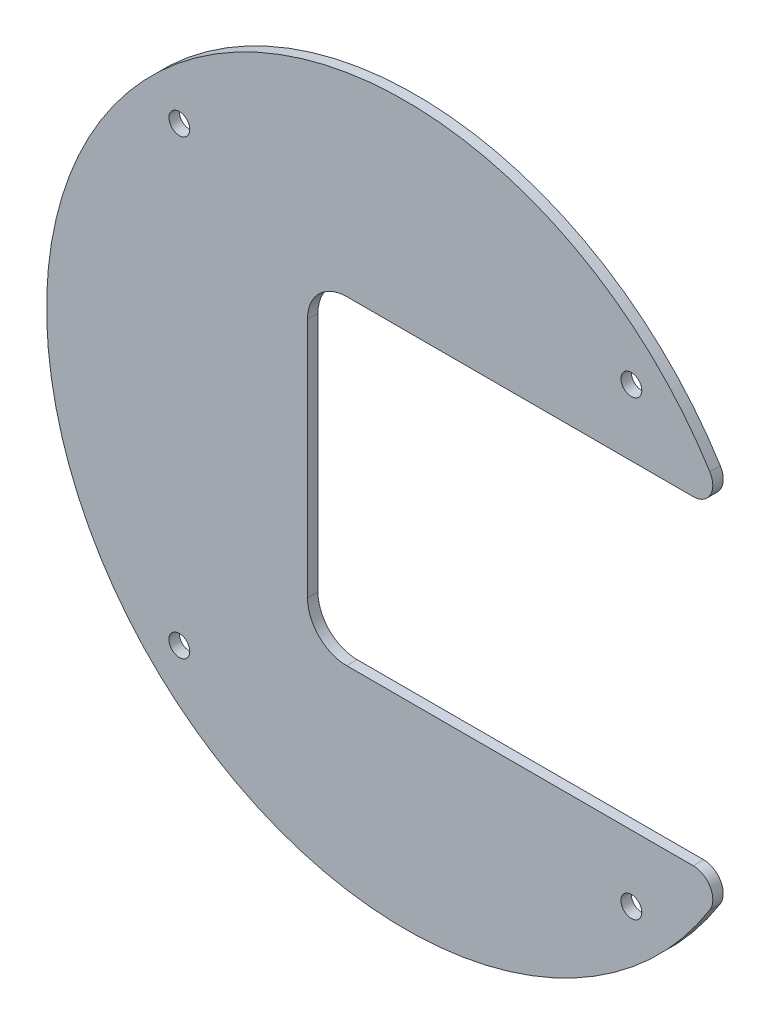
SolidWorks part; units mm, degrees
ref_plane "Front Plane" through (0, 0, 0) normal (0, 0, 1) x (1, 0, 0)
ref_plane "Top Plane" through (0, 0, 0) normal (0, 1, 0) x (1, 0, 0)
ref_plane "Right Plane" through (0, 0, 0) normal (1, 0, 0) x (0, 0, -1)
sketch "草圖1" plane through (0, 0, 0) normal (0, 0, 1) x (1, 0, 0)
  line L0 (49.2418, -24.5) -> (-15, -24.5)
  line L1 (-15, -24.5) -> (-15, 24.5)
  line L2 (-15, 24.5) -> (49.2418, 24.5)
  arc A0 (49.2418, 24.5) -> (49.2418, -24.5) centre (0, 0) ccw
  circle A1 centre (34.6482, 34.6482) radius 1.6
  circle A2 centre (-34.6482, 34.6482) radius 1.6
  circle A3 centre (-34.6482, -34.6482) radius 1.6
  circle A4 centre (34.6482, -34.6482) radius 1.6
extrude "填料-伸長1" add sketch "草圖1" along normal blind 1.6
fillet "圓角1" radius 6 2 edges at (-15, 24.5, 0.8) (-15, -24.5, 0.8)
fillet "圓角2" radius 3 2 edges at (49.2418, 24.5, 0.8) (49.2418, -24.5, 0.8)
